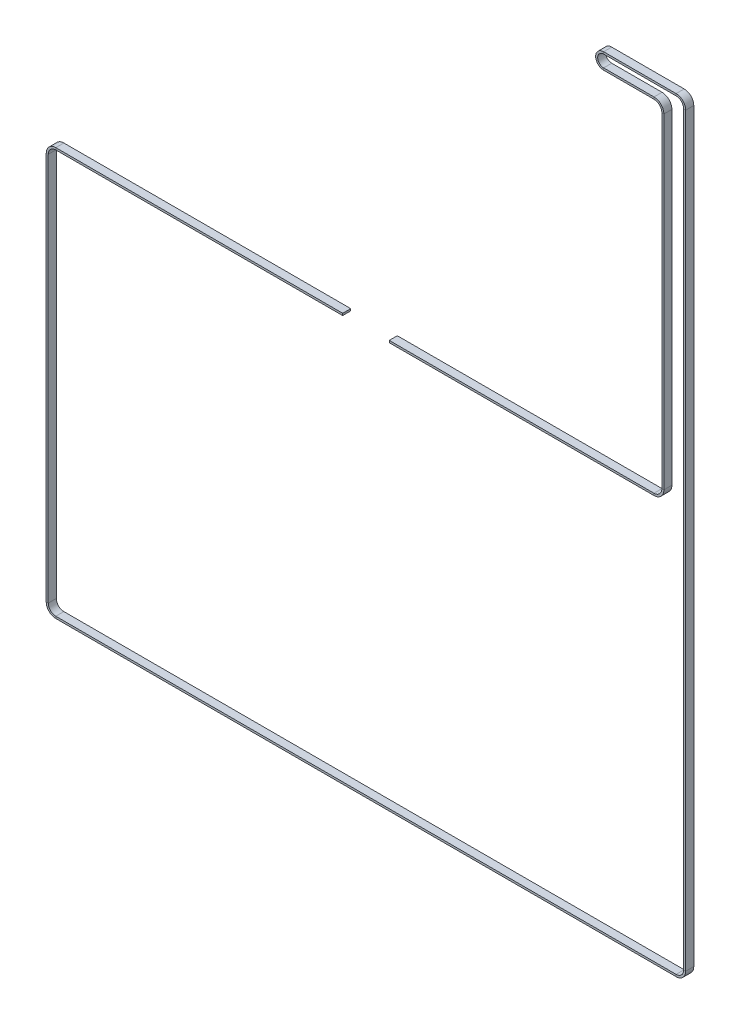
SolidWorks part; units mm, degrees
ref_plane "Front" through (0, 0, 0) normal (0, 0, 1) x (1, 0, 0)
ref_plane "Top" through (0, 0, 0) normal (0, 1, 0) x (1, 0, 0)
ref_plane "Right" through (0, 0, 0) normal (1, 0, 0) x (0, 0, -1)
sketch "Sketch1" plane through (0, 0, 2.2) normal (0, 0, 1) x (1, 0, 0)
  line L0 (377.3122, -142.2854) -> (431.3122, -142.2854)
  line L1 (377.3122, -152.6854) -> (414.8122, -152.6854)
  line L2 (421.4122, -159.2854) -> (421.4122, -401.6854)
  line L3 (437.6872, -148.6604) -> (437.6872, -703.9854)
  line L4 (-37.0628, -703.9854) -> (-37.0628, -414.5104)
  line L5 (431.3122, -710.3604) -> (-30.6878, -710.3604)
  line L6 (-30.6878, -408.1354) -> (182.9622, -408.1354)
  line L7 (217.6622, -406.6854) -> (217.6622, -411.6854) construction
  line L9 (414.8122, -408.2854) -> (217.6622, -408.2854)
  line L10 (182.9622, -411.6854) -> (182.9622, -406.6854) construction
  circle A0 centre (414.8122, -159.2854) radius 6.6 construction
  circle A1 centre (431.3122, -148.6604) radius 6.375 construction
  circle A2 centre (377.3122, -147.4854) radius 5.2 construction
  arc A3 (431.3122, -142.2854) -> (437.6872, -148.6604) centre (431.3122, -148.6604) cw
  arc A4 (377.3122, -152.6854) -> (377.3122, -142.2854) centre (377.3122, -147.4854) cw
  arc A5 (414.8122, -152.6854) -> (421.4122, -159.2854) centre (414.8122, -159.2854) cw
  circle A6 centre (-30.6878, -703.9854) radius 6.375 construction
  arc A7 (-30.6878, -710.3604) -> (-37.0628, -703.9854) centre (-30.6878, -703.9854) cw
  circle A8 centre (431.3122, -148.6604) radius 9 construction
  circle A9 centre (414.8122, -159.2854) radius 9 construction
  circle A11 centre (431.3122, -703.9854) radius 6.375 construction
  arc A12 (437.6872, -703.9854) -> (431.3122, -710.3604) centre (431.3122, -703.9854) cw
  arc A13 (-37.0628, -414.5104) -> (-30.6878, -408.1354) centre (-30.6878, -414.5104) cw
  arc A15 (421.4122, -401.6854) -> (414.8122, -408.2854) centre (414.8122, -401.6854) cw
  circle A16 centre (-30.6878, -414.5104) radius 6.375 construction
  circle A17 centre (-30.6878, -414.5104) radius 5.9875 construction
  circle A18 centre (414.8122, -401.6854) radius 6.6 construction
  circle A19 centre (414.8122, -401.6854) radius 5.9875 construction
  dimension "D1" = 12.75
ref_plane "Plane1" through (182.9622, -408.1354, 2.2) normal (1, 0, 0) x (0, 0, -1)
sketch "Sketch4" plane through (182.9622, -408.1354, 2.2) normal (1, 0, 0) x (0, 0, -1)
  line L0 (0, 259.475) -> (0, -295.85) construction
  line L1 (3, -0.75) -> (-3, -0.75)
  line L2 (3, -0.75) -> (3, 0.75)
  line L3 (3, 0.75) -> (-3, 0.75)
  line L4 (-3, -0.75) -> (-3, 0.75)
  line L5 (3, -0.75) -> (-3, 0.75) construction
  line L6 (3, 0.75) -> (-3, -0.75) construction
  point P0 (0, 0)
  dimension "D1" = 1.5
  dimension "D2" = 6
sweep "Sweep1" add profiles "Sketch4" path "Sketch1"
